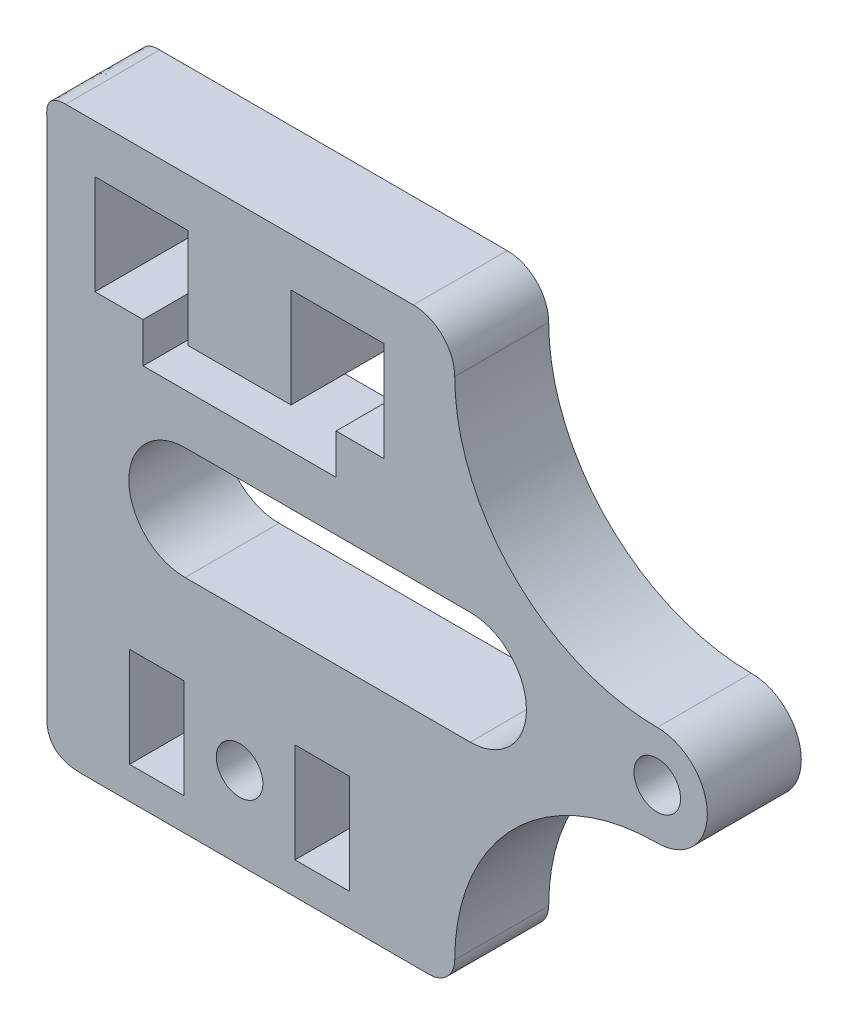
SolidWorks part; units mm, degrees
material "Acrylic (Medium-high impact)"
ref_plane "Front Plane" through (0, 0, 0) normal (0, 0, 1) x (1, 0, 0)
ref_plane "Top Plane" through (0, 0, 0) normal (0, 1, 0) x (1, 0, 0)
ref_plane "Right Plane" through (0, 0, 0) normal (1, 0, 0) x (0, 0, -1)
sketch "Sketch1" plane through (0, 0, 0) normal (0, 0, 1) x (1, 0, 0)
  line L0 (405.5669, 551.2389) -> (405.5669, 553.7389)
  line L1 (396.3551, 553.7389) -> (402.763, 553.7389)
  line L2 (393.5512, 553.7389) -> (393.5512, 551.2389)
  line L3 (393.5512, 551.2389) -> (405.5669, 551.2389)
  line L4 (390.5551, 559.9389) -> (390.5551, 553.7389)
  line L5 (393.5512, 553.7389) -> (390.5551, 553.7389)
  line L6 (396.3551, 559.9389) -> (390.5551, 559.9389)
  line L7 (396.3551, 553.7389) -> (396.3551, 559.9389)
  line L8 (405.5669, 553.7389) -> (408.563, 553.7389)
  line L9 (408.563, 553.7389) -> (408.563, 559.9389)
  line L10 (402.763, 559.9389) -> (402.763, 553.7389)
  line L11 (408.563, 559.9389) -> (402.763, 559.9389)
  line L12 (392.709, 535.5389) -> (392.709, 529.3389)
  line L13 (392.709, 529.3389) -> (396.109, 529.3389)
  line L14 (396.109, 535.5389) -> (392.709, 535.5389)
  line L15 (396.109, 529.3389) -> (396.109, 535.5389)
  line L16 (403.009, 529.3389) -> (406.4091, 529.3389)
  line L17 (406.4091, 529.3389) -> (406.4091, 535.5389)
  line L18 (403.009, 535.5389) -> (403.009, 529.3389)
  line L19 (406.4091, 535.5389) -> (403.009, 535.5389)
  line L20 (388.7293, 562.9389) -> (410.3746, 562.9389)
  line L21 (387.5551, 561.7659) -> (387.5551, 529.5109)
  line L22 (389.7293, 527.3389) -> (411.3746, 527.3389)
  line L23 (-605.591, 535.5389) -> (49394.409, 535.5389) construction
  line L24 (396.1657, 548.1389) -> (413.9157, 548.1389)
  line L25 (396.1657, 541.1389) -> (413.9157, 541.1389)
  line L26 (-600.441, 544.6389) -> (49399.559, 544.6389) construction
  line L27 (398.109, 532.4389) -> (396.109, 532.4389) construction
  line L28 (401.009, 532.4389) -> (403.009, 532.4389) construction
  line L29 (399.559, -466.6171) -> (399.559, 49533.3829) construction
  line L30 (425.559, -455.7473) -> (425.559, 49544.2527) construction
  line L31 (-608.8734, 553.7389) -> (49391.1266, 553.7389) construction
  line L32 (421.909, 544.6389) -> (421.909, 535.5389) construction
  line L33 (421.909, 544.6389) -> (421.909, 553.7389) construction
  line L34 (412.9514, 560.3621) -> (412.9514, 528.9157) construction
  circle A0 centre (425.559, 544.6389) radius 1.45
  arc A1 (396.1657, 548.1389) -> (396.1657, 541.1389) centre (396.1657, 544.6389) ccw
  circle A2 centre (399.559, 532.4389) radius 1.45
  arc A3 (412.9514, 528.9157) -> (425.559, 541.5233) centre (425.559, 528.9157) cw
  arc A4 (412.9514, 560.3621) -> (425.559, 547.7545) centre (425.559, 560.3621) ccw
  arc A5 (425.559, 547.7545) -> (425.559, 541.5233) centre (425.559, 544.6389) cw
  arc A7 (413.9157, 548.1389) -> (413.9157, 541.1389) centre (413.9157, 544.6389) cw
  arc A8 (411.3746, 527.3389) -> (412.9514, 528.9157) centre (411.3746, 528.9157) ccw
  arc A9 (410.3746, 562.9389) -> (412.9514, 560.3621) centre (410.3746, 560.3621) cw
  spline S36 degree 2 poles (387.5551, 561.7659) (387.4905, 562.9389) (388.7293, 562.9389) knots 0 0 0 1 1 1
  spline S37 degree 2 poles (387.5551, 529.5109) (387.4355, 527.3389) (389.7293, 527.3389) knots 0 0 0 1 1 1
  point P26 (399.559, 544.6389)
  point P30 (399.559, 553.7389)
  point P38 (394.409, 535.5389)
  point P40 (412.9514, 544.6389)
  dimension "D5" = 2.9
  dimension "D12" = 6.2
  dimension "D18" = 6.4078
  dimension "D2" = 3.4
  dimension "D3" = 5.8
  dimension "D4" = 2.5
  dimension "D6" = 2
  dimension "D7" = 18.2
  dimension "D8" = 2
  dimension "D9" = 3
  dimension "D10" = 3
  dimension "D11" = 26
  dimension "D13" = 12.0157
  dimension "D14" = 32.2551
  dimension "D15" = 31.4465
  dimension "D17" = 17.75
  dimension "D19" = 13.3924
  dimension "D20" = 22.35
  dimension "D21" = 7
extrude "Boss-Extrude2" add sketch "Sketch1" along normal blind 5.85
